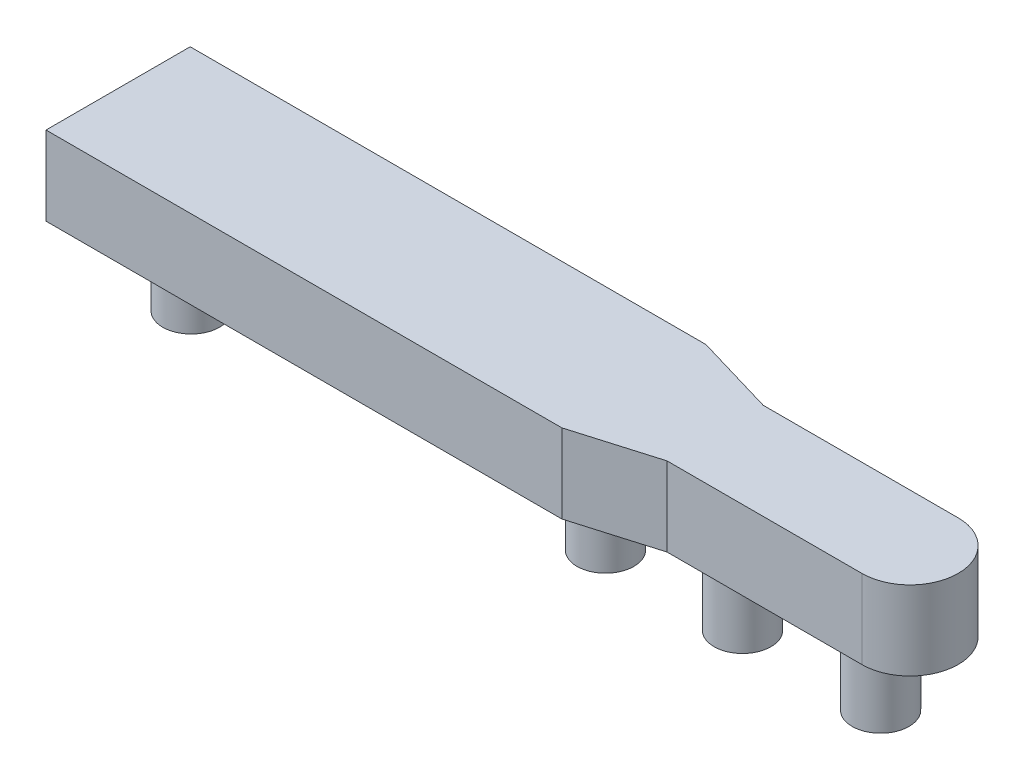
SolidWorks part; units mm, degrees
ref_plane "Front Plane" through (0, 0, 0) normal (0, 0, 1) x (1, 0, 0)
ref_plane "Top Plane" through (0, 0, 0) normal (0, 1, 0) x (1, 0, 0)
ref_plane "Right Plane" through (0, 0, 0) normal (1, 0, 0) x (0, 0, -1)
sketch "Sketch1" plane through (0, 0, 0) normal (0, 0, 1) x (1, 0, 0)
  line L1 (-17.469, 9.1211) -> (86.531, 9.1211)
  line L2 (-17.469, 9.1211) -> (-17.469, -0.5989)
  line L3 (-17.469, -0.5989) -> (86.531, -0.5989)
  line L4 (86.531, 9.1211) -> (86.531, -0.5989)
  dimension "D1" = 9.72
  dimension "D2" = 104
extrude "body" add sketch "Sketch1" along normal blind 17.75
sketch "Sketch2" plane through (0, -0.5989, 0) normal (0, -1, 0) x (1, 0, 0)
  line L7 (80.031, 17.75) -> (80.031, 0) construction
  line L8 (46.031, 17.75) -> (56.031, 14.8)
  line L9 (56.031, 14.8) -> (80.031, 14.8)
  line L10 (80.031, 2.95) -> (56.031, 2.95)
  line L11 (46.031, 0) -> (56.031, 2.95)
  line L12 (46.031, 17.75) -> (86.531, 17.75)
  line L13 (86.531, 17.75) -> (86.531, 0)
  line L14 (86.531, 0) -> (46.031, 0)
  line L15 (-17.469, 17.75) -> (86.531, 17.75) construction
  line L16 (86.531, 17.75) -> (86.531, 0) construction
  line L17 (-17.469, 17.75) -> (-17.469, 0) construction
  line L18 (-17.469, 0) -> (86.531, 0) construction
  arc A1 (80.031, 2.95) -> (80.031, 14.8) centre (80.031, 8.875) ccw
  dimension "D2" = 24
  dimension "D3" = 24
  dimension "D4" = 6.5
  dimension "D5" = 63.5
  dimension "D6" = 11.85
  dimension "D7" = 0
  dimension "D8" = 0
  dimension "D9" = 63.5
  dimension "D10" = 0
extrude "front_cut_out" cut sketch "Sketch2" against normal through all
sketch "Sketch4" plane through (0, -0.5989, 0) normal (0, -1, 0) x (1, 0, 0)
  line L0 (-17.469, 0) -> (46.031, 0) construction
  line L1 (-17.469, 17.75) -> (-17.469, 0) construction
  line L2 (-8.469, 17.75) -> (-8.469, 0) construction
  line L3 (-17.469, 17.75) -> (46.031, 17.75) construction
  circle A0 centre (-8.469, 8.875) radius 3.5
  circle A1 centre (42.531, 8.875) radius 3.5
  circle A2 centre (59.5309, 9) radius 3.5
  circle A3 centre (76.5309, 9) radius 3.5
  dimension "D1" = 7
  dimension "D2" = 51
  dimension "D4" = 9
  dimension "D5" = 9
  dimension "D6" = 9
  dimension "D7" = 68
  dimension "D8" = 85
extrude "Boss-Extrude2" add sketch "Sketch4" along normal blind 9.5
